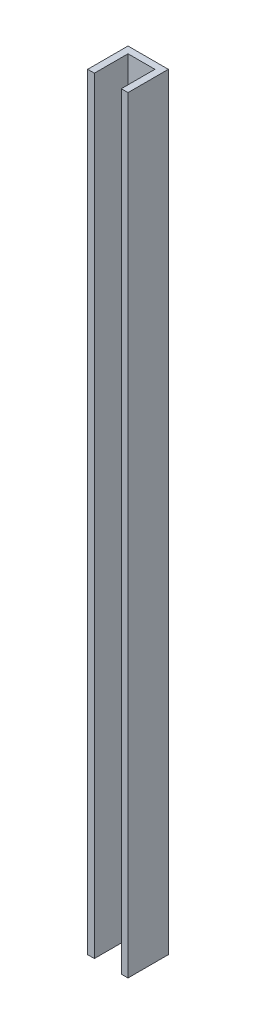
SolidWorks part; units mm, degrees
material "Plain Carbon Steel"
ref_plane "Front Plane" through (0, 0, 0) normal (0, 0, 1) x (1, 0, 0)
ref_plane "Top Plane" through (0, 0, 0) normal (0, 1, 0) x (1, 0, 0)
ref_plane "Right Plane" through (0, 0, 0) normal (1, 0, 0) x (0, 0, -1)
sketch "Sketch1" plane through (0, 0, 0) normal (0, 1, 0) x (1, 0, 0)
  line L0 (0, 0) -> (0, 19.05)
  line L1 (0, 19.05) -> (19.05, 19.05)
  line L2 (19.05, 19.05) -> (19.05, 0)
  line L3 (19.05, 0) -> (15.875, 0)
  line L4 (15.875, 0) -> (15.875, 15.875)
  line L5 (15.875, 15.875) -> (3.175, 15.875)
  line L6 (3.175, 15.875) -> (3.175, 0)
  line L7 (3.175, 0) -> (0, 0)
extrude "Boss-Extrude1" add sketch "Sketch1" along normal blind 361.95
